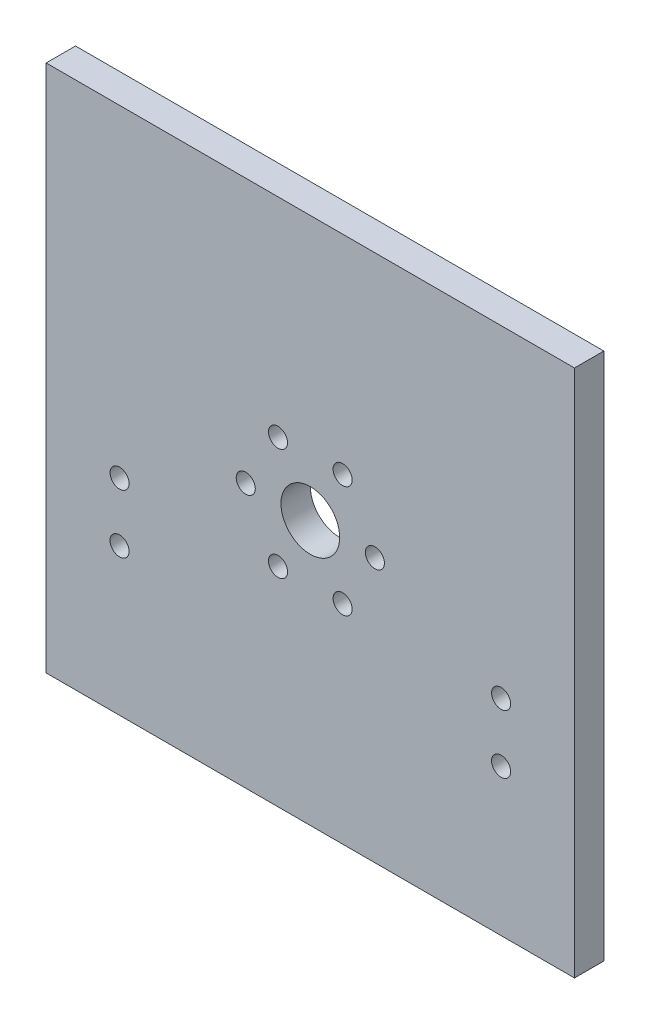
SolidWorks part; units mm, degrees
material "6061-T6 (SS)"
ref_plane "前视基准面" through (0, 0, 0) normal (0, 0, 1) x (1, 0, 0)
ref_plane "上视基准面" through (0, 0, 0) normal (0, 1, 0) x (1, 0, 0)
ref_plane "右视基准面" through (0, 0, 0) normal (1, 0, 0) x (0, 0, -1)
other "Configuration Table"
sketch "草图1" plane through (0, 0, 0) normal (0, 0, 1) x (1, 0, 0)
  line L0 (-90, -90) -> (90, -90)
  line L1 (90, -90) -> (90, 90)
  line L2 (90, 90) -> (-90, 90)
  line L3 (-90, 90) -> (-90, -90)
extrude "凸台-拉伸1" add sketch "草图1" along normal blind 10
sketch "草图2" plane through (0, 0, 0) normal (0, 0, -1) x (-1, 0, 0)
  circle A0 centre (0, 0) radius 10
  circle A1 centre (-22, 0) radius 3.25
  circle A2 centre (-11, 19.0526) radius 3.25
  circle A3 centre (11, 19.0526) radius 3.25
  circle A4 centre (22, 0) radius 3.25
  circle A5 centre (11, -19.0526) radius 3.25
  circle A6 centre (-11, -19.0526) radius 3.25
  circle A7 centre (65, -20) radius 3.25
  circle A8 centre (65, -40) radius 3.25
  circle A9 centre (-65, -20) radius 3.25
  circle A10 centre (-65, -40) radius 3.25
extrude "切除-拉伸1" cut sketch "草图2" against normal blind 11
